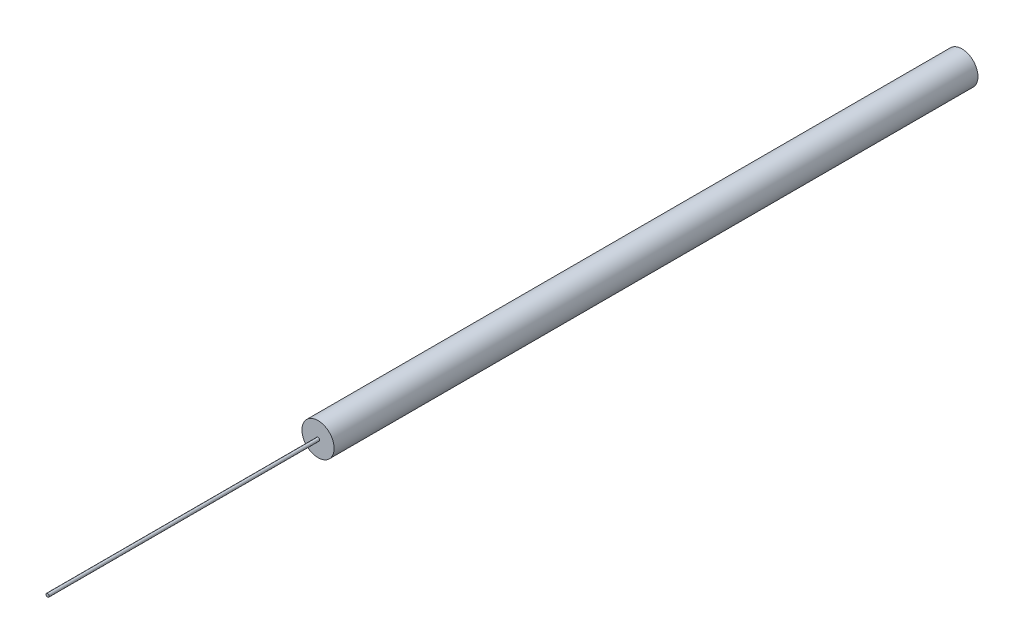
SolidWorks part; units mm, degrees
ref_plane "前视基准面" through (0, 0, 0) normal (0, 0, 1) x (1, 0, 0)
ref_plane "上视基准面" through (0, 0, 0) normal (0, 1, 0) x (1, 0, 0)
ref_plane "右视基准面" through (0, 0, 0) normal (1, 0, 0) x (0, 0, -1)
other "Configuration Table"
sketch "草图1" plane through (0, 0, 0) normal (0, 0, 1) x (1, 0, 0)
  circle A0 centre (0, 0) radius 5
extrude "凸台-拉伸1" add sketch "草图1" along normal blind 200
sketch "草图2" plane through (0, 0, 200) normal (0, 0, 1) x (1, 0, 0)
  circle A0 centre (0, 0) radius 0.5
extrude "凸台-拉伸2" add sketch "草图2" along normal blind 84 contours A0
